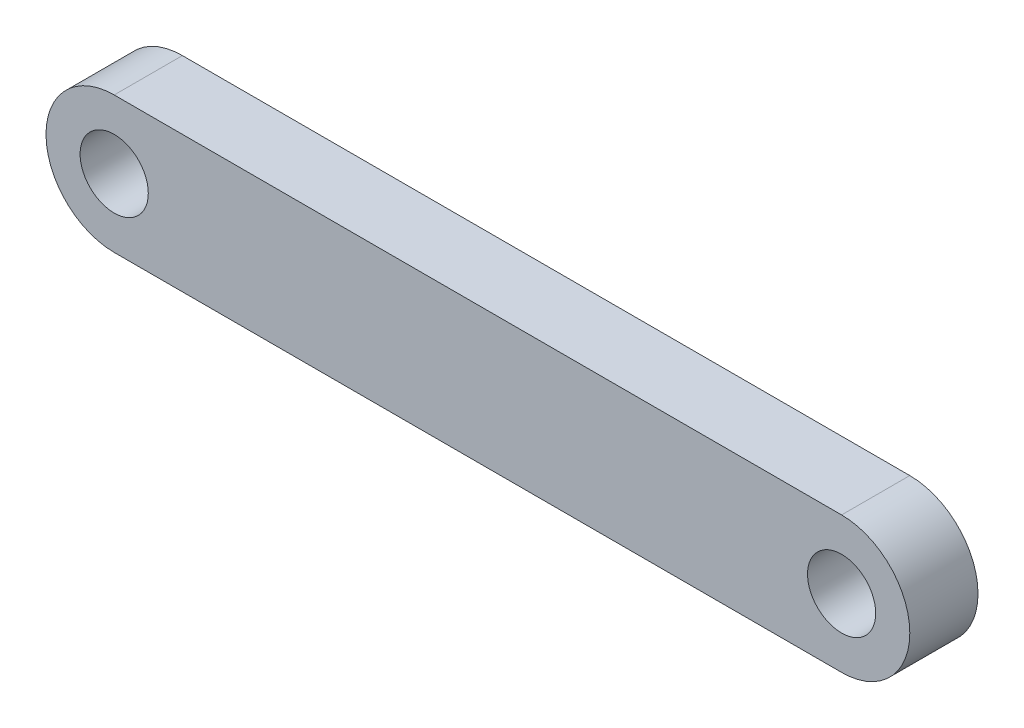
SolidWorks part; units mm, degrees
ref_plane "Front Plane" through (0, 0, 0) normal (0, 0, 1) x (1, 0, 0)
ref_plane "Top Plane" through (0, 0, 0) normal (0, 1, 0) x (1, 0, 0)
ref_plane "Right Plane" through (0, 0, 0) normal (1, 0, 0) x (0, 0, -1)
sketch "Sketch1" plane through (0, 0, 0) normal (0, 0, 1) x (1, 0, 0)
  line L0 (0, 0) -> (-32, 0)
  dimension "D1" = 32
sketch "Sketch2" plane through (0, 0, 0) normal (0, 0, 1) x (1, 0, 0)
  line L0 (-32, 3) -> (0, 3)
  line L1 (-32, -3) -> (0, -3)
  circle A0 centre (-32, 0) radius 1.5
  circle A1 centre (0, 0) radius 1.5
  arc A2 (-32, 3) -> (-32, -3) centre (-32, 0) ccw
  arc A3 (0, -3) -> (0, 3) centre (0, 0) ccw
  dimension "D1" = 3
  dimension "D2" = 6
  dimension "D3" = 3
  dimension "D4" = 6
extrude "Boss-Extrude1" add sketch "Sketch2" along normal blind 3
